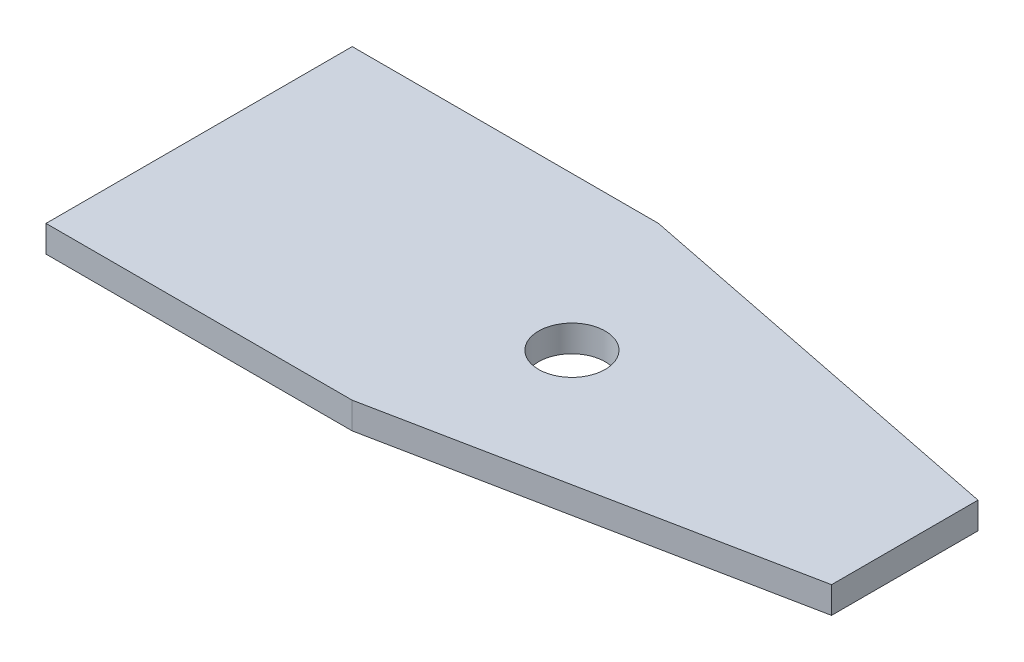
SolidWorks part; units mm, degrees
ref_plane "前视基准面" through (0, 0, 0) normal (0, 0, 1) x (1, 0, 0)
ref_plane "上视基准面" through (0, 0, 0) normal (0, 1, 0) x (1, 0, 0)
ref_plane "右视基准面" through (0, 0, 0) normal (1, 0, 0) x (0, 0, -1)
sketch "草图1" plane through (0, 0, 0) normal (0, 1, 0) x (1, 0, 0)
  line L0 (53, 11.5) -> (28, 11.5) construction
  line L1 (0, 0) -> (53, 0)
  line L2 (0, 0) -> (0, 23)
  line L3 (0, 23) -> (53, 23)
  line L4 (53, 0) -> (53, 23)
  circle A0 centre (28, 11.5) radius 2.5
  dimension "D4" = 5
  dimension "D1" = 53
  dimension "D2" = 23
  dimension "D3" = 25
extrude "凸台-拉伸1" add sketch "草图1" along normal blind 2
sketch "草图2" plane through (0, 2, 0) normal (0, 1, 0) x (1, 0, 0)
  line L0 (53, 23) -> (53, 17)
  line L1 (53, 0) -> (53, 23) construction
  line L2 (53, 17) -> (24.7357, 22.6529) construction
  line L3 (53, 17) -> (23, 23)
  line L4 (53, 23) -> (0, 23) construction
  line L5 (23, 0) -> (23, 23) construction
  line L6 (23, 23) -> (53, 23)
  line L7 (23, 0) -> (53, 6)
  line L8 (0, 0) -> (53, 0) construction
  line L9 (53, 6) -> (24.7357, 0.3471) construction
  line L10 (53, 6) -> (53, 0)
  line L11 (53, 0) -> (23, 0)
extrude "切除-拉伸1" cut sketch "草图2" against normal blind 2
